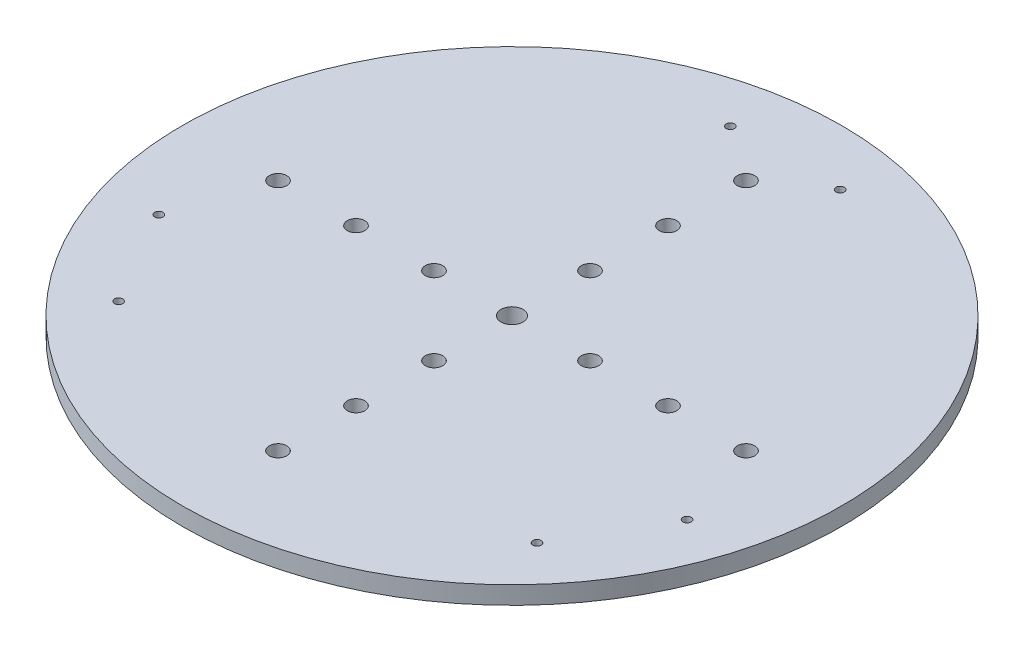
SolidWorks part; units mm, degrees
ref_plane "Alzado" through (0, 0, 0) normal (0, 0, 1) x (1, 0, 0)
ref_plane "Planta" through (0, 0, 0) normal (0, 1, 0) x (1, 0, 0)
ref_plane "Vista lateral" through (0, 0, 0) normal (1, 0, 0) x (0, 0, -1)
sketch "Croquis1" plane through (0, 0, 0) normal (0, 1, 0) x (1, 0, 0)
  circle A0 centre (0, 0) radius 120
  dimension "D1" = 240
extrude "Saliente-Extruir1" add sketch "Croquis1" along normal blind 6.5
sketch "Croquis2" plane through (0, 6.5, 0) normal (0, 1, 0) x (1, 0, 0)
  circle A0 centre (0, 0) radius 4
  dimension "D1" = 8
extrude "Cortar-Extruir1" cut sketch "Croquis2" against normal blind 6.5
sketch "Croquis3" plane through (0, 0, 0) normal (0, -1, 0) x (-1, 0, 0)
  line L0 (-25.225, 0) -> (-31.575, 0) construction
  line L1 (0, -120) -> (0, 120) construction
  line L2 (-53.625, 0) -> (-59.975, 0) construction
  line L3 (-82.025, 0) -> (-88.375, 0) construction
  line L4 (82.025, 0) -> (88.375, 0) construction
  line L5 (53.625, 0) -> (59.975, 0) construction
  line L6 (25.225, 0) -> (31.575, 0) construction
  line L7 (120, 0) -> (-120, 0) construction
  circle A0 centre (0, 0) radius 120 construction
  circle A1 centre (-28.4, 0) radius 3.175
  circle A2 centre (0, 0) radius 4 construction
  circle A3 centre (-56.8, 0) radius 3.175
  circle A4 centre (-85.2, 0) radius 3.175
  circle A5 centre (85.2, 0) radius 3.175
  circle A6 centre (56.8, 0) radius 3.175
  circle A7 centre (28.4, 0) radius 3.175
  circle A8 centre (0, -28.4) radius 3.175
  circle A9 centre (0, -56.8) radius 3.175
  circle A10 centre (0, -85.2) radius 3.175
  circle A11 centre (0, 85.2) radius 3.175
  circle A12 centre (0, 56.8) radius 3.175
  circle A13 centre (0, 28.4) radius 3.175
  dimension "D1" = 6.35
  dimension "D3" = 6.35
  dimension "D4" = 28.4
  dimension "D5" = 6.35
  dimension "D6" = 28.4
  dimension "D7" = 6.35
  dimension "D8" = 28.4
  dimension "D9" = 6.35
  dimension "D10" = 28.4
  dimension "D11" = 6.35
  dimension "D12" = 28.4
  dimension "D2" = 28.4
extrude "Cortar-Extruir2" cut sketch "Croquis3" against normal blind 6.5
sketch "Croquis4" plane through (0, 0, 0) normal (0, -1, 0) x (1, 0, 0)
  line L0 (0, 0) -> (0, -120) construction
  circle A0 centre (0, 0) radius 120 construction
  circle A1 centre (20, -99.5056) radius 1.5
  circle A2 centre (-20, -99.5056) radius 1.5
  circle A3 centre (-96.1744, 32.4323) radius 1.5
  circle A4 centre (-76.1744, 67.0733) radius 1.5
  circle A5 centre (76.1744, 67.0733) radius 1.5
  circle A6 centre (96.1744, 32.4323) radius 1.5
  point P21 (0, 0)
  dimension "D1" = 3
  dimension "D2" = 20
  dimension "D3" = 3
extrude "Cortar-Extruir3" cut sketch "Croquis4" against normal blind 10
